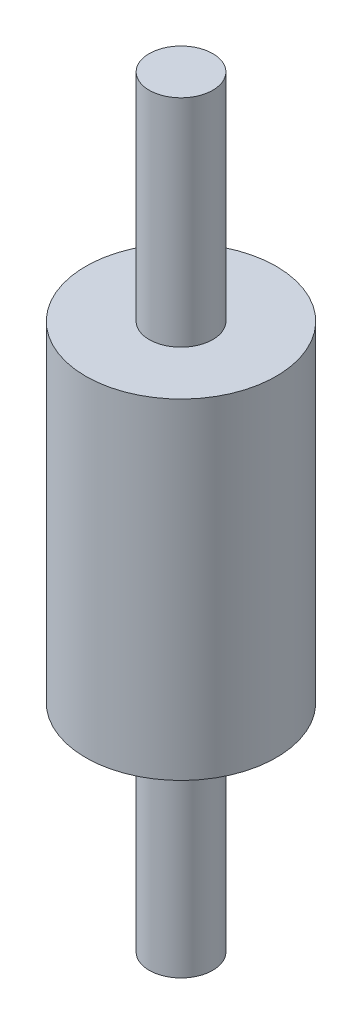
SolidWorks part; units mm, degrees
ref_plane "Front Plane" through (0, 0, 0) normal (0, 0, 1) x (1, 0, 0)
ref_plane "Top Plane" through (0, 0, 0) normal (0, 1, 0) x (1, 0, 0)
ref_plane "Right Plane" through (0, 0, 0) normal (1, 0, 0) x (0, 0, -1)
sketch "Sketch1" plane through (0, 0, 0) normal (1, 0, 0) x (0, 0, -1)
  line L0 (0, -30) -> (2.5, -30)
  line L1 (2.5, -30) -> (2.5, -13)
  line L2 (2.5, -13) -> (7.5, -13)
  line L3 (7.5, -13) -> (7.5, 13)
  line L4 (7.5, 13) -> (2.5, 13)
  line L5 (2.5, 13) -> (2.5, 30)
  line L6 (2.5, 30) -> (0, 30)
  line L7 (0, 30) -> (0, -30)
  line L8 (0, 0) -> (0, 62.5912) construction
  dimension "D1" = 26
  dimension "D2" = 5
  dimension "D3" = 5
  dimension "D4" = 15
  dimension "D5" = 17
revolve "Revolve1" add sketch "Sketch1" angle 360 about L8
cosmetic thread "Cosmetic Thread1"
cosmetic thread "Cosmetic Thread2"
